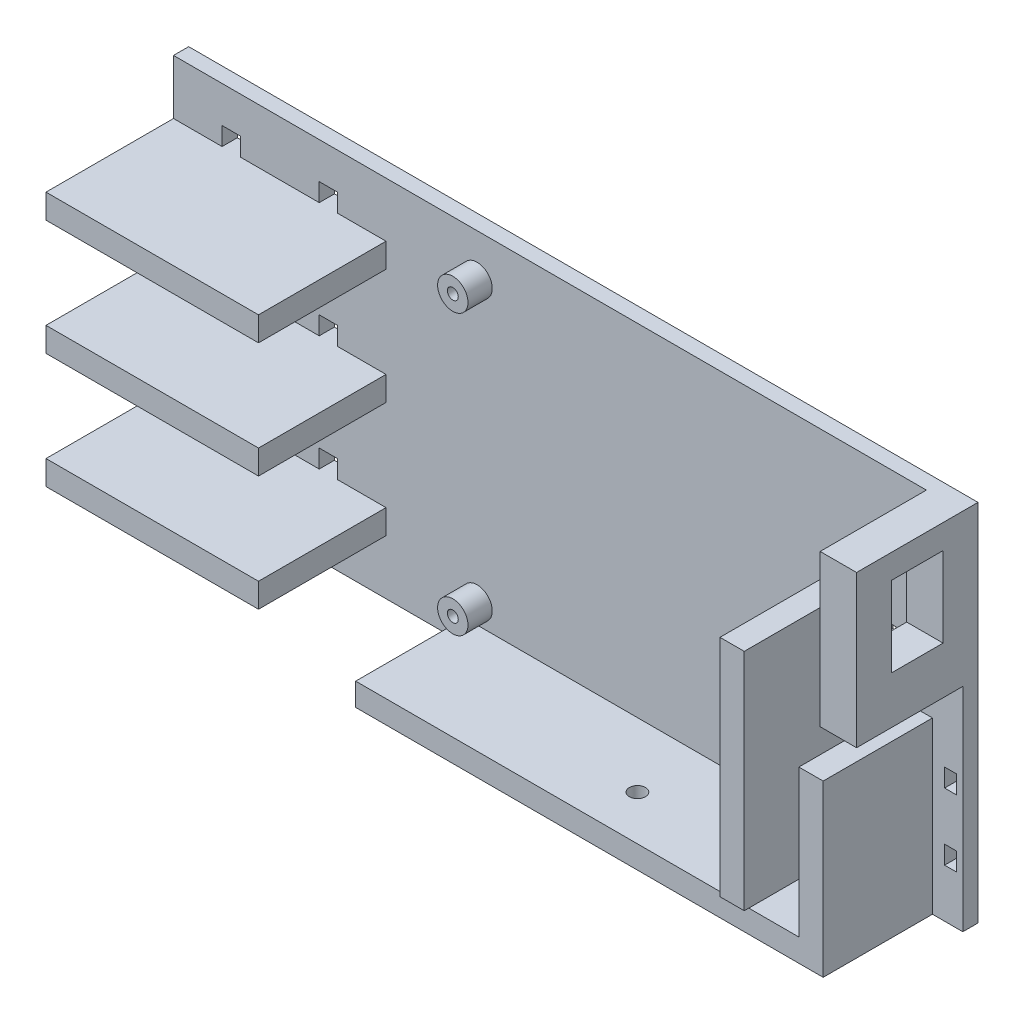
SolidWorks part; units mm, degrees
material "ABS"
ref_plane "Front Plane" through (0, 0, 0) normal (0, 0, 1) x (1, 0, 0)
ref_plane "Top Plane" through (0, 0, 0) normal (0, 1, 0) x (1, 0, 0)
ref_plane "Right Plane" through (0, 0, 0) normal (1, 0, 0) x (0, 0, -1)
sketch "Sketch1" plane through (0, 0, 0) normal (0, 0, 1) x (1, 0, 0)
  line L1 (0, 0) -> (130, 0)
  line L2 (0, 0) -> (0, 60)
  line L3 (0, 60) -> (130, 60)
  line L4 (130, 0) -> (130, 60)
  dimension "D1" = 130
  dimension "D2" = 60
extrude "Boss-Extrude1" add sketch "Sketch1" along normal blind 2.5
sketch "Sketch2" plane through (0, 0, 2.5) normal (0, 0, 1) x (1, 0, 0)
  line L0 (0, 60) -> (0, 0) construction
  line L2 (130, 60) -> (0, 60) construction
  circle A0 centre (50, 7) radius 2.5
  circle A1 centre (105, 7) radius 2.5
  circle A2 centre (50, 53) radius 2.5
  point P6 (12.5666, 33.2833)
  point P8 (12.5666, 6.6198)
  point P9 (0, 0)
  point P14 (19.5438, 50.6625)
  point P15 (0, 0)
  dimension "D1" = 55
  dimension "D3" = 5
  dimension "D4" = 50
  dimension "D5" = 7
  dimension "D2" = 46
extrude "Boss-Extrude2" add sketch "Sketch2" along normal blind 4
sketch "Sketch3" plane through (0, 0, 2.5) normal (0, 0, 1) x (1, 0, 0)
  line L0 (0, 0) -> (130, 0) construction
  line L1 (110, 42) -> (114, 42)
  line L2 (110, 42) -> (110, 5)
  line L3 (110, 5) -> (114, 5)
  line L4 (114, 42) -> (114, 5)
  line L5 (130, 0) -> (130, 60) construction
  dimension "D1" = 37
  dimension "D2" = 4
  dimension "D3" = 5
  dimension "D4" = 16
extrude "Boss-Extrude3" add sketch "Sketch3" along normal blind 20
sketch "Sketch4" plane through (0, 0, 2.5) normal (0, 0, 1) x (1, 0, 0)
  line L0 (0, 0) -> (130, 0) construction
  line L1 (121, 28) -> (125, 28)
  line L2 (121, 28) -> (121, 0)
  line L3 (121, 0) -> (125, 0)
  line L4 (125, 28) -> (125, 0)
  line L5 (130, 0) -> (130, 60) construction
  dimension "D1" = 4
  dimension "D2" = 5
  dimension "D3" = 28
extrude "Boss-Extrude4" add sketch "Sketch4" along normal blind 18
sketch "Sketch5" plane through (0, 0, 6.5) normal (0, 0, 1) x (1, 0, 0)
  circle A0 centre (105, 7) radius 0.9
  circle A1 centre (50, 7) radius 0.9
  circle A2 centre (50, 53) radius 0.9
  dimension "D1" = 1.8
extrude "Cut-Extrude1" cut sketch "Sketch5" against normal through all
sketch "Sketch6" plane through (0, 0, 2.5) normal (0, 0, 1) x (1, 0, 0)
  line L0 (110, 42) -> (110, 5) construction
  line L1 (107, 38) -> (110, 38)
  line L2 (107, 38) -> (107, 35)
  line L3 (107, 35) -> (110, 35)
  line L4 (110, 38) -> (110, 35)
  line L5 (110, 42) -> (110, 5) construction
  line L6 (107, 11) -> (110, 11)
  line L7 (107, 11) -> (107, 8)
  line L8 (107, 8) -> (110, 8)
  line L9 (110, 11) -> (110, 8)
  line L10 (110, 5) -> (114, 5) construction
  line L11 (114, 42) -> (110, 42) construction
  line L12 (121, 28) -> (121, 0) construction
  line L13 (119.5, 22) -> (121, 22)
  line L14 (119.5, 22) -> (119.5, 19)
  line L15 (119.5, 19) -> (121, 19)
  line L16 (121, 22) -> (121, 19)
  line L17 (125, 0) -> (125, 28) construction
  line L18 (127, 22) -> (129, 22)
  line L19 (127, 22) -> (127, 19)
  line L20 (127, 19) -> (129, 19)
  line L21 (129, 22) -> (129, 19)
  line L22 (0, 0) -> (121, 0) construction
  line L23 (127, 11) -> (129, 11)
  line L24 (127, 11) -> (127, 8)
  line L25 (127, 8) -> (129, 8)
  line L26 (129, 11) -> (129, 8)
  line L27 (121, 11) -> (119.5, 11)
  line L28 (121, 11) -> (121, 8)
  line L29 (121, 8) -> (119.5, 8)
  line L30 (119.5, 11) -> (119.5, 8)
  line L31 (125, 28) -> (121, 28) construction
  line L32 (114, 5) -> (114, 42) construction
  line L33 (116, 11) -> (118, 11)
  line L34 (116, 11) -> (116, 8)
  line L35 (116, 8) -> (118, 8)
  line L36 (118, 11) -> (118, 8)
  line L37 (116, 38) -> (119, 38)
  line L38 (116, 38) -> (116, 35)
  line L39 (116, 35) -> (119, 35)
  line L40 (119, 38) -> (119, 35)
  point P40 (127, 20.5)
  dimension "D1" = 3
  dimension "D2" = 3
  dimension "D3" = 3
  dimension "D4" = 3
  dimension "D5" = 3
  dimension "D6" = 4
  dimension "D7" = 2
  dimension "D8" = 1.5
  dimension "D9" = 3
  dimension "D10" = 3
  dimension "D11" = 3
  dimension "D12" = 3
  dimension "D13" = 8
  dimension "D14" = 6
  dimension "D15" = 2
  dimension "D16" = 2
  dimension "D17" = 3
  dimension "D18" = 3
  dimension "D19" = 3
  dimension "D20" = 2
extrude "Cut-Extrude2" cut sketch "Sketch6" against normal through all
sketch "Sketch7" plane through (130, 0, 0) normal (1, 0, 0) x (0, 0, -1)
  line L1 (0, 60) -> (-20, 60)
  line L2 (0, 60) -> (0, 35)
  line L3 (0, 35) -> (-20, 35)
  line L4 (-20, 60) -> (-20, 35)
  line L5 (-14.25, 42.8) -> (-5.75, 42.8)
  line L6 (-14.25, 42.8) -> (-14.25, 56)
  line L7 (-14.25, 56) -> (-5.75, 56)
  line L8 (-5.75, 42.8) -> (-5.75, 56)
  point P9 (-10, 42.8)
  point P10 (-10, 35)
  dimension "D1" = 20
  dimension "D2" = 25
  dimension "D3" = 13.2
  dimension "D4" = 8.5
  dimension "D5" = 4
extrude "Boss-Extrude5" add sketch "Sketch7" against normal blind 6
sketch "Sketch8" plane through (0, 0, 2.5) normal (0, 0, 1) x (1, 0, 0)
  line L0 (0, 60) -> (0, 0) construction
  line L1 (0, 51) -> (35, 51)
  line L2 (0, 51) -> (0, 47)
  line L3 (0, 47) -> (35, 47)
  line L4 (35, 51) -> (35, 47)
  line L5 (0, 32) -> (35, 32)
  line L6 (0, 32) -> (0, 28)
  line L7 (0, 28) -> (35, 28)
  line L8 (35, 32) -> (35, 28)
  line L9 (0, 13) -> (35, 13)
  line L10 (0, 13) -> (0, 9)
  line L11 (0, 9) -> (35, 9)
  line L12 (35, 13) -> (35, 9)
  point P14 (0, 30)
  point P15 (0, 30)
  dimension "D1" = 4
  dimension "D2" = 15
  dimension "D3" = 15
  dimension "D4" = 35
extrude "Boss-Extrude6" add sketch "Sketch8" along normal blind 21
sketch "Sketch9" plane through (0, 0, 2.5) normal (0, 0, 1) x (1, 0, 0)
  line L0 (35, 13) -> (0, 13) construction
  line L1 (8, 13) -> (11, 13)
  line L2 (8, 13) -> (8, 16)
  line L3 (8, 16) -> (11, 16)
  line L4 (11, 13) -> (11, 16)
  line L5 (35, 32) -> (0, 32) construction
  line L6 (24, 13) -> (27, 13)
  line L7 (24, 13) -> (24, 16)
  line L8 (24, 16) -> (27, 16)
  line L9 (27, 13) -> (27, 16)
  line L10 (8, 32) -> (11, 32)
  line L11 (8, 32) -> (8, 35)
  line L12 (8, 35) -> (11, 35)
  line L13 (11, 32) -> (11, 35)
  line L14 (35, 51) -> (0, 51) construction
  line L15 (24, 32) -> (27, 32)
  line L16 (24, 32) -> (24, 35)
  line L17 (24, 35) -> (27, 35)
  line L18 (27, 32) -> (27, 35)
  line L19 (8, 51) -> (11, 51)
  line L20 (8, 51) -> (8, 54)
  line L21 (8, 54) -> (11, 54)
  line L22 (11, 51) -> (11, 54)
  line L23 (0, 47) -> (0, 32) construction
  line L24 (24, 51) -> (27, 51)
  line L25 (24, 51) -> (24, 54)
  line L26 (24, 54) -> (27, 54)
  line L27 (27, 51) -> (27, 54)
  line L28 (35, 28) -> (35, 32) construction
  line L29 (0, 47) -> (35, 47) construction
  line L30 (8, 7) -> (10.5, 7)
  line L31 (8, 7) -> (8, 4)
  line L32 (8, 4) -> (10.5, 4)
  line L33 (10.5, 7) -> (10.5, 4)
  line L34 (8, 26) -> (10.5, 26)
  line L35 (8, 26) -> (8, 23)
  line L36 (8, 23) -> (10.5, 23)
  line L37 (10.5, 26) -> (10.5, 23)
  line L38 (24, 26) -> (27, 26)
  line L39 (24, 26) -> (24, 23)
  line L40 (24, 23) -> (27, 23)
  line L41 (27, 26) -> (27, 23)
  line L42 (24, 4) -> (27, 4)
  line L43 (24, 4) -> (24, 7)
  line L44 (24, 7) -> (27, 7)
  line L45 (27, 4) -> (27, 7)
  line L46 (24, 45) -> (27, 45)
  line L47 (24, 45) -> (24, 42)
  line L48 (24, 42) -> (27, 42)
  line L49 (27, 45) -> (27, 42)
  line L50 (8, 45) -> (10.5, 45)
  line L51 (8, 45) -> (8, 42)
  line L52 (8, 42) -> (10.5, 42)
  line L53 (10.5, 45) -> (10.5, 42)
  line L54 (0, 28) -> (35, 28) construction
  line L55 (0, 9) -> (35, 9) construction
  dimension "D1" = 3
  dimension "D2" = 3
  dimension "D3" = 3
  dimension "D4" = 8
  dimension "D5" = 8
  dimension "D6" = 2
  dimension "D7" = 2
  dimension "D8" = 2
  dimension "D9" = 3
  dimension "D10" = 3
  dimension "D11" = 2.5
extrude "Cut-Extrude3" cut sketch "Sketch9" against normal through all
sketch "Sketch11" plane through (0, 0, 0) normal (0, -1, 0) x (1, 0, 0)
  line L1 (125, 20.5) -> (48, 20.5)
  line L2 (125, 20.5) -> (125, 0)
  line L3 (125, 0) -> (48, 0)
  line L4 (48, 20.5) -> (48, 0)
  dimension "D1" = 77
extrude "Boss-Extrude8" add sketch "Sketch11" against normal blind 3.75
sketch "Sketch12" plane through (0, 0, 0) normal (0, -1, 0) x (1, 0, 0)
  circle A0 centre (87.03, 13.12) radius 1.325
  dimension "D1" = 2.65
extrude "Cut-Extrude4" cut sketch "Sketch12" against normal through all
equation "\"D3@Sketch8\"=\"D2@Sketch8\""
equation "\"D3@Sketch9\"=\"D1@Sketch9\""
